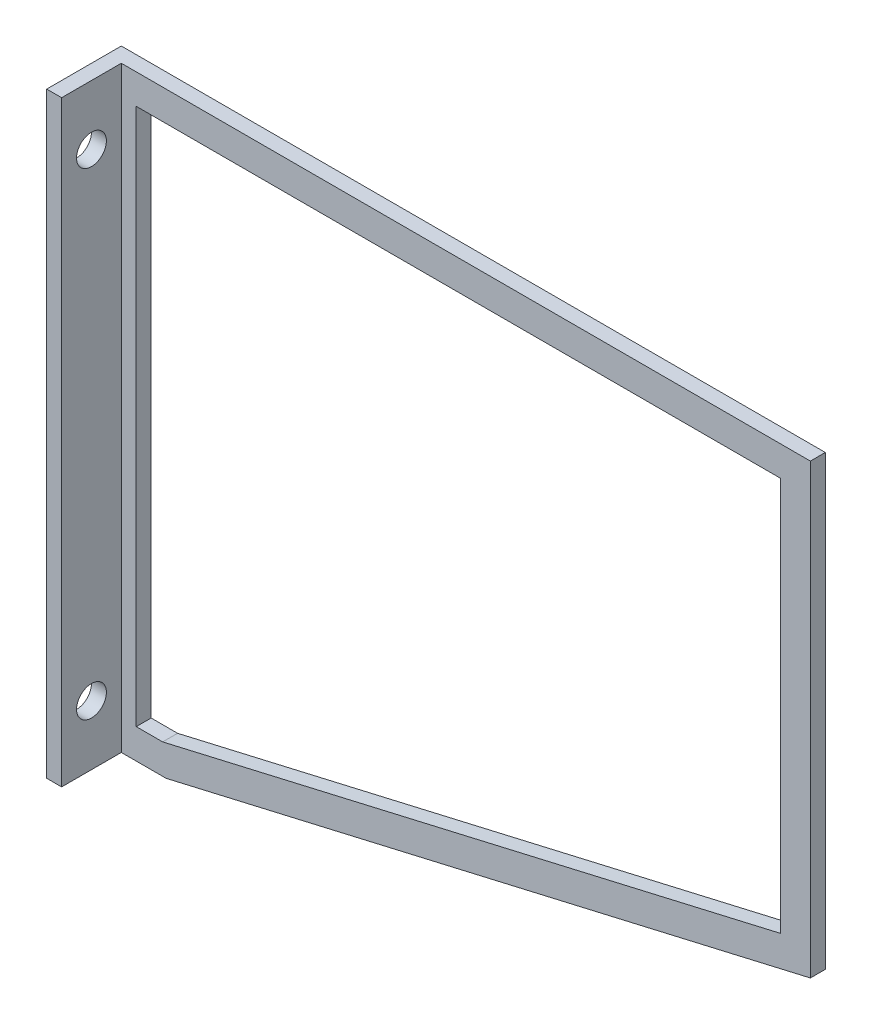
SolidWorks part; units mm, degrees
material "1060 Alloy"
ref_plane "Front Plane" through (0, 0, 0) normal (0, 0, 1) x (1, 0, 0)
ref_plane "Top Plane" through (0, 0, 0) normal (0, 1, 0) x (1, 0, 0)
ref_plane "Right Plane" through (0, 0, 0) normal (1, 0, 0) x (0, 0, -1)
sketch "Sketch1" plane through (0, 0, 0) normal (0, 0, 1) x (1, 0, 0)
  line L0 (0, 0) -> (20, 0)
  line L1 (20, 0) -> (235.8806, 50)
  line L2 (235.8806, 50) -> (235.8806, 200)
  line L3 (235.8806, 200) -> (0, 200)
  line L4 (0, 200) -> (0, 0)
  line L5 (10, 190) -> (225.8806, 190)
  line L6 (225.8806, 190) -> (225.8806, 57.9486)
  line L7 (225.8806, 57.9486) -> (18.8571, 10)
  line L8 (18.8571, 10) -> (10, 10)
  line L9 (10, 10) -> (10, 190)
  dimension "D1" = 200
  dimension "D2" = 150
  dimension "D3" = 20
  dimension "D4" = 10
  dimension "D5" = 10
  dimension "D6" = 10
  dimension "D7" = 10
  dimension "D8" = 10
extrude "Boss-Extrude1" add sketch "Sketch1" along normal blind 5
sketch "Sketch2" plane through (0, 0, 5) normal (0, 0, 1) x (1, 0, 0)
  line L0 (0, 0) -> (20, 0) construction
  line L1 (0, 200) -> (5, 200)
  line L2 (0, 200) -> (0, 0)
  line L3 (0, 0) -> (5, 0)
  line L4 (5, 200) -> (5, 0)
  dimension "D1" = 5
extrude "Boss-Extrude2" add sketch "Sketch2" along normal blind 20
sketch "Sketch3" plane through (5, 0, 0) normal (1, 0, 0) x (0, 0, -1)
  line L0 (-25, 0) -> (-25, 200) construction
  line L1 (-25, 0) -> (-5, 0) construction
  line L2 (-25, 200) -> (-5, 200) construction
  circle A0 centre (-15, 180) radius 5
  circle A1 centre (-15, 20) radius 5
  dimension "D1" = 10
  dimension "D2" = 10
  dimension "D3" = 10
  dimension "D4" = 10
  dimension "D5" = 20
  dimension "D6" = 20
extrude "Cut-Extrude1" cut sketch "Sketch3" against normal through all
